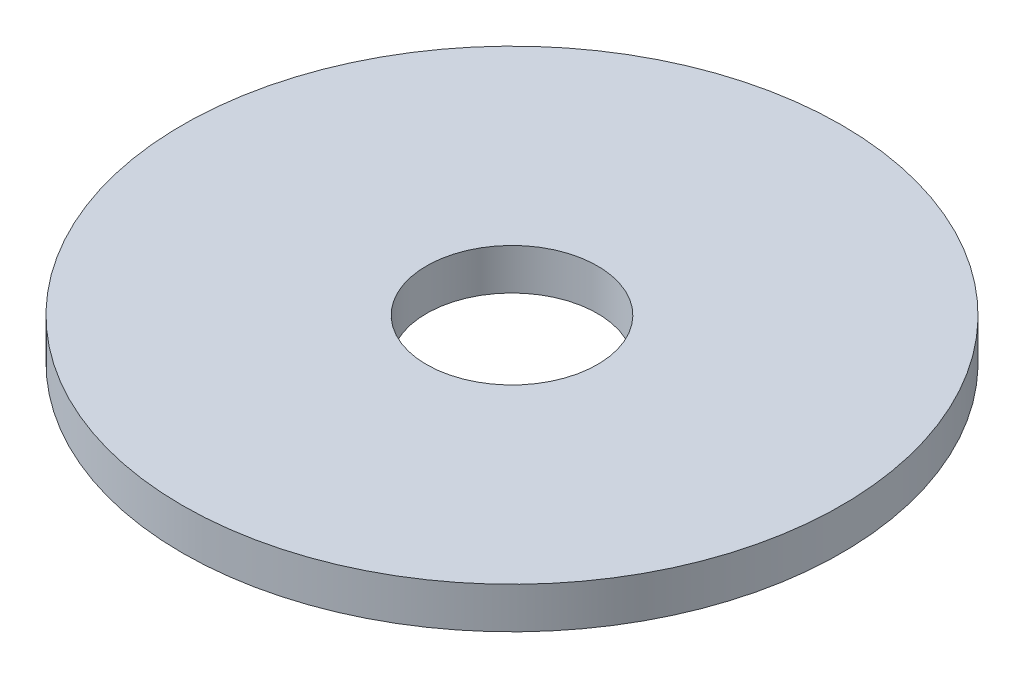
SolidWorks part; units mm, degrees
ref_plane "Front Plane" through (0, 0, 0) normal (0, 0, 1) x (1, 0, 0)
ref_plane "Top Plane" through (0, 0, 0) normal (0, 1, 0) x (1, 0, 0)
ref_plane "Right Plane" through (0, 0, 0) normal (1, 0, 0) x (0, 0, -1)
sketch "Sketch2" plane through (0, 0, 0) normal (0, 1, 0) x (1, 0, 0)
  circle A0 centre (0, 0) radius 4.15
  circle A1 centre (0, 0) radius 16
  dimension "D1" = 4.15
  dimension "D2" = 16
extrude "Boss-Extrude1" add sketch "Sketch2" along normal blind 2
